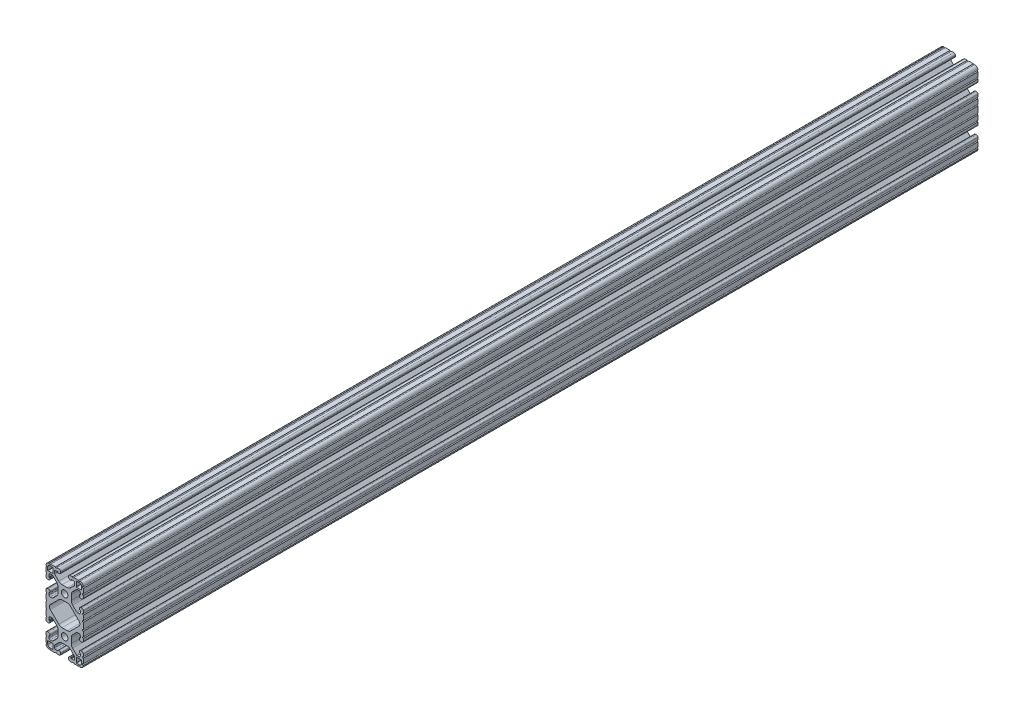
SolidWorks part; units mm, degrees
ref_plane "Front Plane" through (0, 0, 0) normal (0, 0, 1) x (1, 0, 0)
ref_plane "Top Plane" through (0, 0, 0) normal (0, 1, 0) x (1, 0, 0)
ref_plane "Right Plane" through (0, 0, 0) normal (1, 0, 0) x (0, 0, -1)
ref_plane "Plane1" through (0, 0, -914.4) normal (0, 0, -1) x (-1, 0, 0)
sketch "Sketch1" plane through (0, 0, -914.4) normal (0, 0, -1) x (-1, 0, 0)
  line L0 (19.05, -14.3256) -> (19.05, -9.4996)
  line L1 (19.05, -7.9756) -> (19.05, -5.6388)
  line L2 (17.4752, -4.064) -> (16.5608, -4.064)
  line L3 (14.986, -5.6388) -> (14.986, -6.35)
  line L4 (15.24, -6.604) -> (15.7099, -6.604)
  line L5 (15.9639, -6.858) -> (15.9639, -9.017)
  line L6 (14.6939, -10.287) -> (12.9683, -10.287)
  line L7 (12.0703, -9.915) -> (8.1476, -5.9923)
  line L8 (6.7564, -2.6337) -> (6.7564, 2.6337)
  line L9 (8.1476, 5.9923) -> (12.0703, 9.915)
  line L10 (12.9683, 10.287) -> (14.6939, 10.287)
  line L11 (15.9639, 9.017) -> (15.9639, 6.858)
  line L12 (15.7099, 6.604) -> (15.24, 6.604)
  line L13 (14.986, 6.35) -> (14.986, 5.6388)
  line L14 (16.5608, 4.064) -> (17.4752, 4.064)
  line L15 (19.05, 5.6388) -> (19.05, 7.9756)
  line L16 (19.05, 9.4996) -> (19.05, 14.3256)
  line L17 (19.05, 15.8496) -> (19.05, 22.2504)
  line L18 (19.05, 23.7744) -> (19.05, 28.6004)
  line L19 (19.05, 30.1244) -> (19.05, 32.4612)
  line L20 (17.4752, 34.036) -> (16.5608, 34.036)
  line L21 (14.986, 32.4612) -> (14.986, 31.75)
  line L22 (15.24, 31.496) -> (15.7099, 31.496)
  line L23 (15.9639, 31.242) -> (15.9639, 29.083)
  line L24 (14.6939, 27.813) -> (12.9683, 27.813)
  line L25 (12.0703, 28.185) -> (8.1476, 32.1077)
  line L26 (6.7564, 35.4663) -> (6.7564, 40.7337)
  line L27 (8.1476, 44.0923) -> (12.0703, 48.015)
  line L28 (12.9683, 48.387) -> (14.6939, 48.387)
  line L29 (15.9639, 47.117) -> (15.9639, 44.958)
  line L30 (15.7099, 44.704) -> (15.24, 44.704)
  line L31 (14.986, 44.45) -> (14.986, 43.7388)
  line L32 (16.5608, 42.164) -> (17.4752, 42.164)
  line L33 (19.05, 43.7388) -> (19.05, 46.0756)
  line L34 (19.05, 47.5996) -> (19.05, 52.4256)
  line L35 (14.3256, 57.15) -> (9.4996, 57.15)
  line L36 (7.9756, 57.15) -> (5.6388, 57.15)
  line L37 (4.064, 55.5752) -> (4.064, 54.6608)
  line L38 (5.6388, 53.086) -> (6.35, 53.086)
  line L39 (6.604, 53.34) -> (6.604, 53.8099)
  line L40 (6.858, 54.0639) -> (9.017, 54.0639)
  line L41 (10.287, 52.7939) -> (10.287, 51.0683)
  line L42 (9.915, 50.1703) -> (5.9923, 46.2476)
  line L43 (2.6337, 44.8564) -> (-2.6337, 44.8564)
  line L44 (-5.9923, 46.2476) -> (-9.915, 50.1703)
  line L45 (-10.287, 51.0683) -> (-10.287, 52.7939)
  line L46 (-9.017, 54.0639) -> (-6.858, 54.0639)
  line L47 (-6.604, 53.8099) -> (-6.604, 53.34)
  line L48 (-6.35, 53.086) -> (-5.6388, 53.086)
  line L49 (-4.064, 54.6608) -> (-4.064, 55.5752)
  line L50 (-5.6388, 57.15) -> (-7.9756, 57.15)
  line L51 (-9.4996, 57.15) -> (-14.3256, 57.15)
  line L52 (-19.05, 52.4256) -> (-19.05, 47.5996)
  line L53 (-19.05, 46.0756) -> (-19.05, 43.7388)
  line L54 (-17.4752, 42.164) -> (-16.5608, 42.164)
  line L55 (-14.986, 43.7388) -> (-14.986, 44.45)
  line L56 (-15.24, 44.704) -> (-15.7099, 44.704)
  line L57 (-15.9639, 44.958) -> (-15.9639, 47.117)
  line L58 (-14.6939, 48.387) -> (-12.9683, 48.387)
  line L59 (-12.0703, 48.015) -> (-8.1476, 44.0923)
  line L60 (-6.7564, 40.7337) -> (-6.7564, 35.4663)
  line L61 (-8.1476, 32.1077) -> (-12.0703, 28.185)
  line L62 (-12.9683, 27.813) -> (-14.6939, 27.813)
  line L63 (-15.9639, 29.083) -> (-15.9639, 31.242)
  line L64 (-15.7099, 31.496) -> (-15.24, 31.496)
  line L65 (-14.986, 31.75) -> (-14.986, 32.4612)
  line L66 (-16.5608, 34.036) -> (-17.4752, 34.036)
  line L67 (-19.05, 32.4612) -> (-19.05, 30.1244)
  line L68 (-19.05, 28.6004) -> (-19.05, 23.7744)
  line L69 (-19.05, 22.2504) -> (-19.05, 15.8496)
  line L70 (-19.05, 14.3256) -> (-19.05, 9.4996)
  line L71 (-19.05, 7.9756) -> (-19.05, 5.6388)
  line L72 (-17.4752, 4.064) -> (-16.5608, 4.064)
  line L73 (-14.986, 5.6388) -> (-14.986, 6.35)
  line L74 (-15.24, 6.604) -> (-15.7099, 6.604)
  line L75 (-15.9639, 6.858) -> (-15.9639, 9.017)
  line L76 (-14.6939, 10.287) -> (-12.9683, 10.287)
  line L77 (-12.0703, 9.915) -> (-8.1476, 5.9923)
  line L78 (-6.7564, 2.6337) -> (-6.7564, -2.6337)
  line L79 (-8.1476, -5.9923) -> (-12.0703, -9.915)
  line L80 (-12.9683, -10.287) -> (-14.6939, -10.287)
  line L81 (-15.9639, -9.017) -> (-15.9639, -6.858)
  line L82 (-15.7099, -6.604) -> (-15.24, -6.604)
  line L83 (-14.986, -6.35) -> (-14.986, -5.6388)
  line L84 (-16.5608, -4.064) -> (-17.4752, -4.064)
  line L85 (-19.05, -5.6388) -> (-19.05, -7.9756)
  line L86 (-19.05, -9.4996) -> (-19.05, -14.3256)
  line L87 (-14.3256, -19.05) -> (-9.4996, -19.05)
  line L88 (-7.9756, -19.05) -> (-5.6388, -19.05)
  line L89 (-4.064, -17.4752) -> (-4.064, -16.5608)
  line L90 (-5.6388, -14.986) -> (-6.35, -14.986)
  line L91 (-6.604, -15.24) -> (-6.604, -15.7099)
  line L92 (-6.858, -15.9639) -> (-9.017, -15.9639)
  line L93 (-10.287, -14.6939) -> (-10.287, -12.9683)
  line L94 (-9.915, -12.0703) -> (-5.9923, -8.1476)
  line L95 (-2.6337, -6.7564) -> (2.6337, -6.7564)
  line L96 (5.9923, -8.1476) -> (9.915, -12.0703)
  line L97 (10.287, -12.9683) -> (10.287, -14.6939)
  line L98 (9.017, -15.9639) -> (6.858, -15.9639)
  line L99 (6.604, -15.7099) -> (6.604, -15.24)
  line L100 (6.35, -14.986) -> (5.6388, -14.986)
  line L101 (4.064, -16.5608) -> (4.064, -17.4752)
  line L102 (5.6388, -19.05) -> (7.9756, -19.05)
  line L103 (9.4996, -19.05) -> (14.3256, -19.05)
  line L104 (-11.8872, -12.1412) -> (-11.8872, -17.018)
  line L105 (-12.1412, -17.272) -> (-15.1384, -17.272)
  line L106 (-17.272, -15.1384) -> (-17.272, -12.1412)
  line L107 (-17.018, -11.8872) -> (-12.1412, -11.8872)
  line L108 (-15.1384, 55.372) -> (-12.1412, 55.372)
  line L109 (-11.8872, 55.118) -> (-11.8872, 50.2412)
  line L110 (-12.1412, 49.9872) -> (-17.018, 49.9872)
  line L111 (-17.272, 50.2412) -> (-17.272, 53.2384)
  line L112 (5.9923, 29.9524) -> (14.6189, 21.3259)
  line L113 (14.6189, 16.7741) -> (5.9923, 8.1476)
  line L114 (2.6337, 6.7564) -> (-2.6337, 6.7564)
  line L115 (-5.9923, 8.1476) -> (-14.6189, 16.7741)
  line L116 (-14.6189, 21.3259) -> (-5.9923, 29.9524)
  line L117 (-2.6337, 31.3436) -> (2.6337, 31.3436)
  line L118 (17.272, -12.1412) -> (17.272, -15.1384)
  line L119 (15.1384, -17.272) -> (12.1412, -17.272)
  line L120 (11.8872, -17.018) -> (11.8872, -12.1412)
  line L121 (12.1412, -11.8872) -> (17.018, -11.8872)
  line L122 (12.1412, 55.372) -> (15.1384, 55.372)
  line L123 (17.272, 53.2384) -> (17.272, 50.2412)
  line L124 (17.018, 49.9872) -> (12.1412, 49.9872)
  line L125 (11.8872, 50.2412) -> (11.8872, 55.118)
  circle A0 centre (0, 0) radius 3.3274
  arc A1 (19.05, -15.8496) -> (19.05, -14.3256) centre (19.05, -15.0876) cw
  arc A2 (19.05, -9.4996) -> (19.05, -7.9756) centre (19.05, -8.7376) cw
  arc A3 (19.05, -5.6388) -> (17.4752, -4.064) centre (17.4752, -5.6388) ccw
  arc A4 (16.5608, -4.064) -> (14.986, -5.6388) centre (16.5608, -5.6388) ccw
  arc A5 (14.986, -6.35) -> (15.24, -6.604) centre (15.24, -6.35) ccw
  arc A6 (15.7099, -6.604) -> (15.9639, -6.858) centre (15.7099, -6.858) cw
  arc A7 (15.9639, -9.017) -> (14.6939, -10.287) centre (14.6939, -9.017) cw
  arc A8 (12.9683, -10.287) -> (12.0703, -9.915) centre (12.9683, -9.017) cw
  arc A9 (8.1476, -5.9923) -> (6.7564, -2.6337) centre (11.5062, -2.6337) cw
  arc A10 (6.7564, 2.6337) -> (8.1476, 5.9923) centre (11.5062, 2.6337) cw
  arc A11 (12.0703, 9.915) -> (12.9683, 10.287) centre (12.9683, 9.017) cw
  arc A12 (14.6939, 10.287) -> (15.9639, 9.017) centre (14.6939, 9.017) cw
  arc A13 (15.9639, 6.858) -> (15.7099, 6.604) centre (15.7099, 6.858) cw
  arc A14 (15.24, 6.604) -> (14.986, 6.35) centre (15.24, 6.35) ccw
  arc A15 (14.986, 5.6388) -> (16.5608, 4.064) centre (16.5608, 5.6388) ccw
  arc A16 (17.4752, 4.064) -> (19.05, 5.6388) centre (17.4752, 5.6388) ccw
  arc A17 (19.05, 7.9756) -> (19.05, 9.4996) centre (19.05, 8.7376) cw
  arc A18 (19.05, 14.3256) -> (19.05, 15.8496) centre (19.05, 15.0876) cw
  arc A19 (19.05, 22.2504) -> (19.05, 23.7744) centre (19.05, 23.0124) cw
  arc A20 (19.05, 28.6004) -> (19.05, 30.1244) centre (19.05, 29.3624) cw
  arc A21 (19.05, 32.4612) -> (17.4752, 34.036) centre (17.4752, 32.4612) ccw
  arc A22 (16.5608, 34.036) -> (14.986, 32.4612) centre (16.5608, 32.4612) ccw
  arc A23 (14.986, 31.75) -> (15.24, 31.496) centre (15.24, 31.75) ccw
  arc A24 (15.7099, 31.496) -> (15.9639, 31.242) centre (15.7099, 31.242) cw
  arc A25 (15.9639, 29.083) -> (14.6939, 27.813) centre (14.6939, 29.083) cw
  arc A26 (12.9683, 27.813) -> (12.0703, 28.185) centre (12.9683, 29.083) cw
  arc A27 (8.1476, 32.1077) -> (6.7564, 35.4663) centre (11.5062, 35.4663) cw
  arc A28 (6.7564, 40.7337) -> (8.1476, 44.0923) centre (11.5062, 40.7337) cw
  arc A29 (12.0703, 48.015) -> (12.9683, 48.387) centre (12.9683, 47.117) cw
  arc A30 (14.6939, 48.387) -> (15.9639, 47.117) centre (14.6939, 47.117) cw
  arc A31 (15.9639, 44.958) -> (15.7099, 44.704) centre (15.7099, 44.958) cw
  arc A32 (15.24, 44.704) -> (14.986, 44.45) centre (15.24, 44.45) ccw
  arc A33 (14.986, 43.7388) -> (16.5608, 42.164) centre (16.5608, 43.7388) ccw
  arc A34 (17.4752, 42.164) -> (19.05, 43.7388) centre (17.4752, 43.7388) ccw
  arc A35 (19.05, 46.0756) -> (19.05, 47.5996) centre (19.05, 46.8376) cw
  arc A36 (19.05, 52.4256) -> (19.05, 53.9496) centre (19.05, 53.1876) cw
  arc A37 (19.05, 53.9496) -> (15.8496, 57.15) centre (15.8751, 53.9751) ccw
  arc A38 (15.8496, 57.15) -> (14.3256, 57.15) centre (15.0876, 57.15) cw
  arc A39 (9.4996, 57.15) -> (7.9756, 57.15) centre (8.7376, 57.15) cw
  arc A40 (5.6388, 57.15) -> (4.064, 55.5752) centre (5.6388, 55.5752) ccw
  arc A41 (4.064, 54.6608) -> (5.6388, 53.086) centre (5.6388, 54.6608) ccw
  arc A42 (6.35, 53.086) -> (6.604, 53.34) centre (6.35, 53.34) ccw
  arc A43 (6.604, 53.8099) -> (6.858, 54.0639) centre (6.858, 53.8099) cw
  arc A44 (9.017, 54.0639) -> (10.287, 52.7939) centre (9.017, 52.7939) cw
  arc A45 (10.287, 51.0683) -> (9.915, 50.1703) centre (9.017, 51.0683) cw
  arc A46 (5.9923, 46.2476) -> (2.6337, 44.8564) centre (2.6337, 49.6062) cw
  arc A47 (-2.6337, 44.8564) -> (-5.9923, 46.2476) centre (-2.6337, 49.6062) cw
  arc A48 (-9.915, 50.1703) -> (-10.287, 51.0683) centre (-9.017, 51.0683) cw
  arc A49 (-10.287, 52.7939) -> (-9.017, 54.0639) centre (-9.017, 52.7939) cw
  arc A50 (-6.858, 54.0639) -> (-6.604, 53.8099) centre (-6.858, 53.8099) cw
  arc A51 (-6.604, 53.34) -> (-6.35, 53.086) centre (-6.35, 53.34) ccw
  arc A52 (-5.6388, 53.086) -> (-4.064, 54.6608) centre (-5.6388, 54.6608) ccw
  arc A53 (-4.064, 55.5752) -> (-5.6388, 57.15) centre (-5.6388, 55.5752) ccw
  arc A54 (-7.9756, 57.15) -> (-9.4996, 57.15) centre (-8.7376, 57.15) cw
  arc A55 (-14.3256, 57.15) -> (-15.8496, 57.15) centre (-15.0876, 57.15) cw
  arc A56 (-15.8496, 57.15) -> (-19.05, 53.9496) centre (-15.8751, 53.9751) ccw
  arc A57 (-19.05, 53.9496) -> (-19.05, 52.4256) centre (-19.05, 53.1876) cw
  arc A58 (-19.05, 47.5996) -> (-19.05, 46.0756) centre (-19.05, 46.8376) cw
  arc A59 (-19.05, 43.7388) -> (-17.4752, 42.164) centre (-17.4752, 43.7388) ccw
  arc A60 (-16.5608, 42.164) -> (-14.986, 43.7388) centre (-16.5608, 43.7388) ccw
  arc A61 (-14.986, 44.45) -> (-15.24, 44.704) centre (-15.24, 44.45) ccw
  arc A62 (-15.7099, 44.704) -> (-15.9639, 44.958) centre (-15.7099, 44.958) cw
  arc A63 (-15.9639, 47.117) -> (-14.6939, 48.387) centre (-14.6939, 47.117) cw
  arc A64 (-12.9683, 48.387) -> (-12.0703, 48.015) centre (-12.9683, 47.117) cw
  arc A65 (-8.1476, 44.0923) -> (-6.7564, 40.7337) centre (-11.5062, 40.7337) cw
  arc A66 (-6.7564, 35.4663) -> (-8.1476, 32.1077) centre (-11.5062, 35.4663) cw
  arc A67 (-12.0703, 28.185) -> (-12.9683, 27.813) centre (-12.9683, 29.083) cw
  arc A68 (-14.6939, 27.813) -> (-15.9639, 29.083) centre (-14.6939, 29.083) cw
  arc A69 (-15.9639, 31.242) -> (-15.7099, 31.496) centre (-15.7099, 31.242) cw
  arc A70 (-15.24, 31.496) -> (-14.986, 31.75) centre (-15.24, 31.75) ccw
  arc A71 (-14.986, 32.4612) -> (-16.5608, 34.036) centre (-16.5608, 32.4612) ccw
  arc A72 (-17.4752, 34.036) -> (-19.05, 32.4612) centre (-17.4752, 32.4612) ccw
  arc A73 (-19.05, 30.1244) -> (-19.05, 28.6004) centre (-19.05, 29.3624) cw
  arc A74 (-19.05, 23.7744) -> (-19.05, 22.2504) centre (-19.05, 23.0124) cw
  arc A75 (-19.05, 15.8496) -> (-19.05, 14.3256) centre (-19.05, 15.0876) cw
  arc A76 (-19.05, 9.4996) -> (-19.05, 7.9756) centre (-19.05, 8.7376) cw
  arc A77 (-19.05, 5.6388) -> (-17.4752, 4.064) centre (-17.4752, 5.6388) ccw
  arc A78 (-16.5608, 4.064) -> (-14.986, 5.6388) centre (-16.5608, 5.6388) ccw
  arc A79 (-14.986, 6.35) -> (-15.24, 6.604) centre (-15.24, 6.35) ccw
  arc A80 (-15.7099, 6.604) -> (-15.9639, 6.858) centre (-15.7099, 6.858) cw
  arc A81 (-15.9639, 9.017) -> (-14.6939, 10.287) centre (-14.6939, 9.017) cw
  arc A82 (-12.9683, 10.287) -> (-12.0703, 9.915) centre (-12.9683, 9.017) cw
  arc A83 (-8.1476, 5.9923) -> (-6.7564, 2.6337) centre (-11.5062, 2.6337) cw
  arc A84 (-6.7564, -2.6337) -> (-8.1476, -5.9923) centre (-11.5062, -2.6337) cw
  arc A85 (-12.0703, -9.915) -> (-12.9683, -10.287) centre (-12.9683, -9.017) cw
  arc A86 (-14.6939, -10.287) -> (-15.9639, -9.017) centre (-14.6939, -9.017) cw
  arc A87 (-15.9639, -6.858) -> (-15.7099, -6.604) centre (-15.7099, -6.858) cw
  arc A88 (-15.24, -6.604) -> (-14.986, -6.35) centre (-15.24, -6.35) ccw
  arc A89 (-14.986, -5.6388) -> (-16.5608, -4.064) centre (-16.5608, -5.6388) ccw
  arc A90 (-17.4752, -4.064) -> (-19.05, -5.6388) centre (-17.4752, -5.6388) ccw
  arc A91 (-19.05, -7.9756) -> (-19.05, -9.4996) centre (-19.05, -8.7376) cw
  arc A92 (-19.05, -14.3256) -> (-19.05, -15.8496) centre (-19.05, -15.0876) cw
  arc A93 (-19.05, -15.8496) -> (-15.8496, -19.05) centre (-15.8751, -15.8751) ccw
  arc A94 (-15.8496, -19.05) -> (-14.3256, -19.05) centre (-15.0876, -19.05) cw
  arc A95 (-9.4996, -19.05) -> (-7.9756, -19.05) centre (-8.7376, -19.05) cw
  arc A96 (-5.6388, -19.05) -> (-4.064, -17.4752) centre (-5.6388, -17.4752) ccw
  arc A97 (-4.064, -16.5608) -> (-5.6388, -14.986) centre (-5.6388, -16.5608) ccw
  arc A98 (-6.35, -14.986) -> (-6.604, -15.24) centre (-6.35, -15.24) ccw
  arc A99 (-6.604, -15.7099) -> (-6.858, -15.9639) centre (-6.858, -15.7099) cw
  arc A100 (-9.017, -15.9639) -> (-10.287, -14.6939) centre (-9.017, -14.6939) cw
  arc A101 (-10.287, -12.9683) -> (-9.915, -12.0703) centre (-9.017, -12.9683) cw
  arc A102 (-5.9923, -8.1476) -> (-2.6337, -6.7564) centre (-2.6337, -11.5062) cw
  arc A103 (2.6337, -6.7564) -> (5.9923, -8.1476) centre (2.6337, -11.5062) cw
  arc A104 (9.915, -12.0703) -> (10.287, -12.9683) centre (9.017, -12.9683) cw
  arc A105 (10.287, -14.6939) -> (9.017, -15.9639) centre (9.017, -14.6939) cw
  arc A106 (6.858, -15.9639) -> (6.604, -15.7099) centre (6.858, -15.7099) cw
  arc A107 (6.604, -15.24) -> (6.35, -14.986) centre (6.35, -15.24) ccw
  arc A108 (5.6388, -14.986) -> (4.064, -16.5608) centre (5.6388, -16.5608) ccw
  arc A109 (4.064, -17.4752) -> (5.6388, -19.05) centre (5.6388, -17.4752) ccw
  arc A110 (7.9756, -19.05) -> (9.4996, -19.05) centre (8.7376, -19.05) cw
  arc A111 (14.3256, -19.05) -> (15.8496, -19.05) centre (15.0876, -19.05) cw
  arc A112 (15.8496, -19.05) -> (19.05, -15.8496) centre (15.8751, -15.8751) ccw
  arc A113 (-12.1412, -11.8872) -> (-11.8872, -12.1412) centre (-12.1412, -12.1412) cw
  arc A114 (-11.8872, -17.018) -> (-12.1412, -17.272) centre (-12.1412, -17.018) cw
  arc A115 (-15.1384, -17.272) -> (-17.272, -15.1384) centre (-15.1384, -15.1384) cw
  arc A116 (-17.272, -12.1412) -> (-17.018, -11.8872) centre (-17.018, -12.1412) cw
  arc A117 (-12.1412, 55.372) -> (-11.8872, 55.118) centre (-12.1412, 55.118) cw
  arc A118 (-11.8872, 50.2412) -> (-12.1412, 49.9872) centre (-12.1412, 50.2412) cw
  arc A119 (-17.018, 49.9872) -> (-17.272, 50.2412) centre (-17.018, 50.2412) cw
  arc A120 (-17.272, 53.2384) -> (-15.1384, 55.372) centre (-15.1384, 53.2384) cw
  circle A121 centre (0, 38.1) radius 3.3274
  arc A122 (2.6337, 31.3436) -> (5.9923, 29.9524) centre (2.6337, 26.5938) cw
  arc A123 (14.6189, 21.3259) -> (14.6189, 16.7741) centre (12.343, 19.05) cw
  arc A124 (5.9923, 8.1476) -> (2.6337, 6.7564) centre (2.6337, 11.5062) cw
  arc A125 (-2.6337, 6.7564) -> (-5.9923, 8.1476) centre (-2.6337, 11.5062) cw
  arc A126 (-14.6189, 16.7741) -> (-14.6189, 21.3259) centre (-12.343, 19.05) cw
  arc A127 (-5.9923, 29.9524) -> (-2.6337, 31.3436) centre (-2.6337, 26.5938) cw
  arc A128 (17.018, -11.8872) -> (17.272, -12.1412) centre (17.018, -12.1412) cw
  arc A129 (17.272, -15.1384) -> (15.1384, -17.272) centre (15.1384, -15.1384) cw
  arc A130 (12.1412, -17.272) -> (11.8872, -17.018) centre (12.1412, -17.018) cw
  arc A131 (11.8872, -12.1412) -> (12.1412, -11.8872) centre (12.1412, -12.1412) cw
  arc A132 (15.1384, 55.372) -> (17.272, 53.2384) centre (15.1384, 53.2384) cw
  arc A133 (17.272, 50.2412) -> (17.018, 49.9872) centre (17.018, 50.2412) cw
  arc A134 (12.1412, 49.9872) -> (11.8872, 50.2412) centre (12.1412, 50.2412) cw
  arc A135 (11.8872, 55.118) -> (12.1412, 55.372) centre (12.1412, 55.118) cw
extrude "Boss-Extrude1" add sketch "Sketch1" against normal blind 914.4
